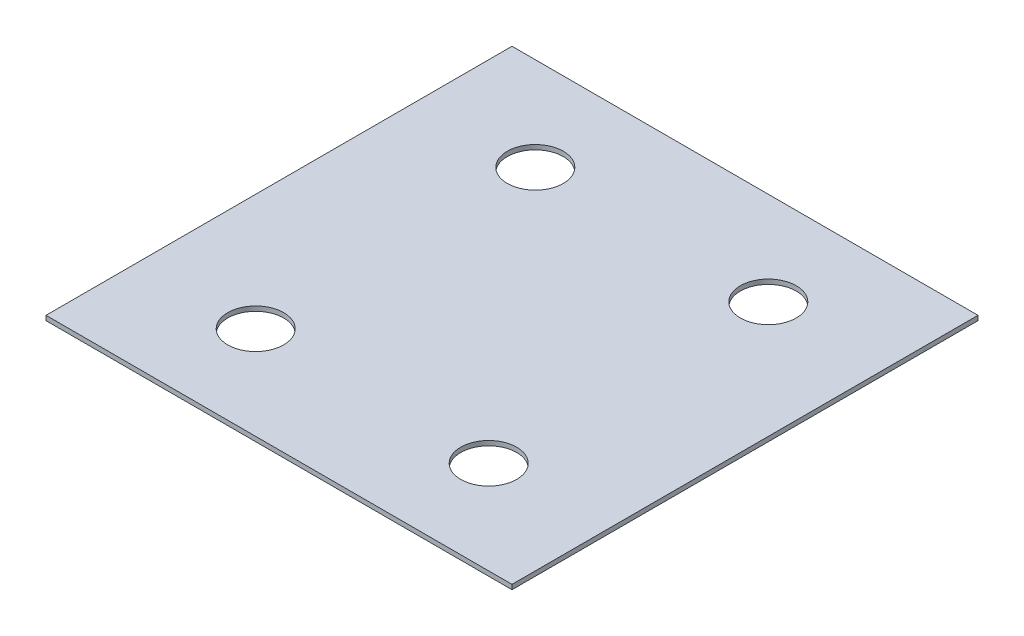
SolidWorks part; units mm, degrees
material "Acrylic (Medium-high impact)"
ref_plane "Front Plane" through (0, 0, 0) normal (0, 0, 1) x (1, 0, 0)
ref_plane "Top Plane" through (0, 0, 0) normal (0, 1, 0) x (1, 0, 0)
ref_plane "Right Plane" through (0, 0, 0) normal (1, 0, 0) x (0, 0, -1)
sketch "Sketch1" plane through (0, 0, 0) normal (0, 1, 0) x (1, 0, 0)
  line L1 (-250, -250) -> (250, -250)
  line L2 (-250, -250) -> (-250, 250)
  line L3 (-250, 250) -> (250, 250)
  line L4 (250, -250) -> (250, 250)
  line L5 (-250, -250) -> (250, 250) construction
  line L6 (-250, 250) -> (250, -250) construction
  point P0 (0, 0)
  dimension "D1" = 500
extrude "Boss-Extrude1" add sketch "Sketch1" along normal blind 5
sketch "Sketch2" plane through (0, 5, 0) normal (0, 1, 0) x (1, 0, 0)
  line L0 (-125, -150) -> (125, -150) construction
  line L1 (-125, -150) -> (125, -150) construction
  line L2 (-125, -150) -> (-125, 150) construction
  line L3 (-125, 150) -> (125, 150) construction
  line L4 (125, -150) -> (125, 150) construction
  line L5 (-125, -150) -> (125, 150) construction
  line L6 (-125, 150) -> (125, -150) construction
  line L7 (-125, -150) -> (-125, 150) construction
  circle A0 centre (-125, -150) radius 30
  circle A1 centre (125, -150) radius 30
  circle A2 centre (125, 150) radius 30
  circle A3 centre (-125, 150) radius 30
  point P0 (0, 0)
  dimension "D3" = 60
  dimension "D1" = 250
  dimension "D2" = 300
  dimension "D6" = 250
  dimension "D7" = 300
  dimension "D4" = 2
  dimension "D5" = 2
extrude "Cut-Extrude1" cut sketch "Sketch2" against normal through all both
